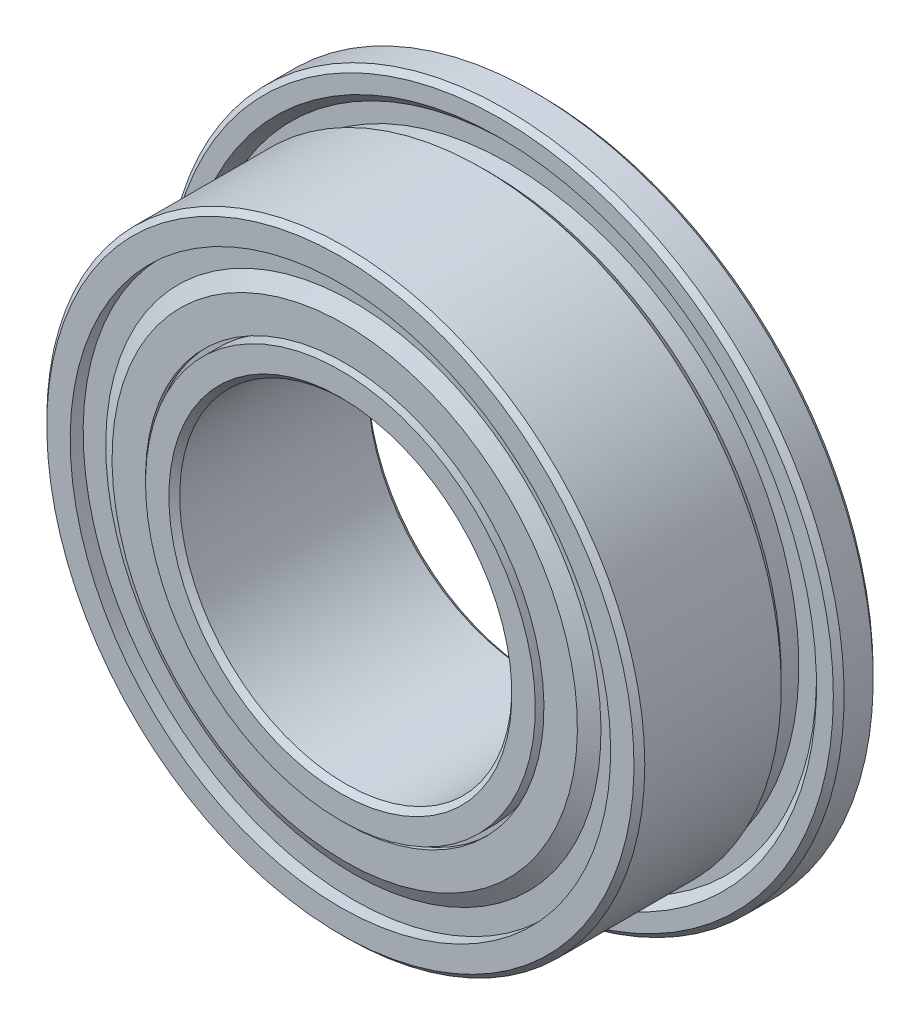
SolidWorks part; units mm, degrees
ref_plane "Front Plane" through (0, 0, 0) normal (0, 0, 1) x (1, 0, 0)
ref_plane "Top Plane" through (0, 0, 0) normal (0, 1, 0) x (1, 0, 0)
ref_plane "Right Plane" through (0, 0, 0) normal (1, 0, 0) x (0, 0, -1)
sketch "Sketch1" plane through (0, 0, 0) normal (1, 0, 0) x (0, 0, -1)
  line L0 (0, 4.5) -> (0, -4.5) construction
  line L1 (-1.5, 4.5) -> (1.5, 4.5) construction
  line L2 (0, 0) -> (1.5, 0) construction
  line L3 (1.5, 5.1) -> (1.5, -5.1) construction
  line L4 (1.5, -5.1) -> (0.9, -5.1) construction
  line L5 (1.5, 2.5) -> (0, 2.5) construction
  line L6 (1.5, 2.5) -> (1.5, -2.5) construction
  dimension "OD" = 9
  dimension "Width" = 3
  dimension "Flange Thickness" = 0.6
  dimension "ID" = 5
  dimension "Flange OD" = 10.2
sketch "Sketch2" plane through (0, 0, 0) normal (1, 0, 0) x (0, 0, -1)
  line L0 (1.5, 5.1) -> (0.9, 5.1)
  line L1 (0.9, 5.1) -> (0.9, 4.7652)
  line L2 (0.6348, 4.5) -> (-1.5, 4.5)
  line L3 (-1.5, 4.5) -> (-1.5, 3.85)
  line L4 (-1.5, 3.85) -> (-0.4873, 3.85)
  line L5 (1.5, 5.1) -> (1.5, -5.1) construction
  line L6 (1.5, 3.85) -> (1.5, 5.1)
  line L7 (1.5, 2.5) -> (-1.5, 2.5)
  line L8 (-1.5, 2.5) -> (-1.5, 3.15)
  line L9 (-1.5, 3.15) -> (-0.4873, 3.15)
  line L10 (1.5, 3.15) -> (1.5, 2.5)
  line L11 (0, 4.5) -> (0, 2.5) construction
  line L12 (-0.6, 3.5) -> (0.6, 3.5) construction
  line L13 (0.4873, 3.85) -> (1.5, 3.85)
  line L14 (0.4873, 3.15) -> (1.5, 3.15)
  line L15 (0.9, 4.7652) -> (1.0326, 4.6326)
  line L16 (1.0326, 4.6326) -> (1.0326, 4.3674)
  line L17 (1.0326, 4.3674) -> (0.7674, 4.3674)
  line L18 (0.7674, 4.3674) -> (0.6348, 4.5)
  line L19 (0.9, 4.5) -> (1.0326, 4.3674) construction
  line L20 (1.0326, 4.6326) -> (0.7674, 4.3674) construction
  line L21 (0.6348, 4.5) -> (0.9, 4.5) construction
  line L22 (0.9, 4.5) -> (0.9, 4.7652) construction
  line L23 (-1.5, 0) -> (1.5, 0) construction
  circle A0 centre (0, 3.5) radius 0.6 construction
  arc A1 (-0.4873, 3.85) -> (0.4873, 3.85) centre (0, 3.5) cw
  arc A2 (-0.4873, 3.15) -> (0.4873, 3.15) centre (0, 3.5) ccw
  dimension "Ball Dia." = 1.2
  dimension "D2" = 135
  dimension "D3" = 0.375
  dimension "Race Thikness" = 0.65
  dimension "D4" = 0.7
revolve "Revolve1" add sketch "Sketch2" angle 360 about L2
fillet "Fillet1" radius 0.0813 3 edges at (0, -5.1, -1.5) (0, -5.1, -0.9) (0, -4.5, 1.5) profile chamfer
sketch "Sketch3" plane through (0, 0, 0) normal (0, 0, 1) x (1, 0, 0)
  line L0 (-2.5, 0) -> (2.5, 0) construction
  line L1 (-4.5, 0) -> (4.5, 0) construction
  point P5 (0, 0)
  dimension "ID2" = 5
  dimension "OD2" = 9
fillet "Fillet2" radius 0.0813 2 edges at (0, -2.5, -1.5) (0, -2.5, 1.5) profile chamfer
sketch "Sketch7" plane through (0, 0, 0) normal (0, 0, 1) x (1, 0, 0)
  line L0 (0, 4.1) -> (0, 2.9)
  line L1 (0, 5.1) -> (0, -5.1) construction
  line L2 (-0.7134, 4.1) -> (0, 0) construction
  line L3 (0, 0) -> (0.7134, 4.1) construction
  line L4 (0.7134, 4.1) -> (-0.7134, 4.1) construction
  circle A0 centre (0, 3.5) radius 0.6 construction
  circle A1 centre (0, 0) radius 4.1 construction
  circle A2 centre (0, 0) radius 2.9 construction
  arc A4 (0, 4.1) -> (0, 2.9) centre (0, 3.5) ccw
  dimension "D1" = 19.742
revolve "Revolve3" add sketch "Sketch7" angle 360 about L0
pattern_circular "CirPattern3" count 14 over 360 about axis through (0, 0, 0) along (0, 0, 1) of bodies 107
sketch "Sketch8" plane through (0, 0, 0) normal (1, 0, 0) x (0, 0, -1)
  line L1 (-1.5, 3.85) -> (-1.24, 3.85)
  line L2 (-1.5, 3.85) -> (-1.5, 4.0667)
  line L3 (-1.5, 4.0667) -> (-1.24, 4.0667)
  line L4 (-1.24, 3.85) -> (-1.24, 4.0667)
  line L5 (1.5, 3.85) -> (1.24, 3.85)
  line L6 (1.5, 3.85) -> (1.5, 4.0667)
  line L7 (1.5, 4.0667) -> (1.24, 4.0667)
  line L8 (1.24, 3.85) -> (1.24, 4.0667)
  line L9 (1.5, 3.15) -> (1.24, 3.15)
  line L10 (1.5, 3.15) -> (1.5, 2.9333)
  line L11 (1.5, 2.9333) -> (1.24, 2.9333)
  line L12 (1.24, 3.15) -> (1.24, 2.9333)
  line L13 (-1.5, 3.15) -> (-1.24, 3.15)
  line L14 (-1.5, 3.15) -> (-1.5, 2.9333)
  line L15 (-1.5, 2.9333) -> (-1.24, 2.9333)
  line L16 (-1.24, 3.15) -> (-1.24, 2.9333)
  dimension "D1" = 0.2167
  dimension "D2" = 0.26
revolve "Cut-Revolve1" cut sketch "Sketch8" angle 360 about L2
sketch "Sketch9" plane through (0, 0, 0) normal (1, 0, 0) x (0, 0, -1)
  line L0 (-1.24, 4.0667) -> (-1.24, 3.7095)
  line L1 (-1.24, 3.7095) -> (-1.37, 3.4844)
  line L2 (-1.37, 3.4844) -> (-1.37, 2.9983)
  line L3 (1.37, 2.9983) -> (1.37, 2.9333) construction
  line L4 (1.24, 4.0667) -> (1.24, 3.7095)
  line L5 (1.24, 3.7095) -> (1.37, 3.4844)
  line L6 (1.37, 3.4844) -> (1.37, 2.9983)
  line L7 (1.5, 2.9333) -> (1.24, 2.9333) construction
  line L8 (-1.305, 4.0667) -> (-1.305, 3.7269)
  line L9 (-1.305, 3.7269) -> (-1.435, 3.5018)
  line L10 (-1.435, 3.5018) -> (-1.435, 2.9983)
  line L11 (-1.24, 4.0667) -> (-1.305, 4.0667)
  line L12 (-1.37, 2.9983) -> (-1.435, 2.9983)
  line L13 (1.305, 4.0667) -> (1.305, 3.7269)
  line L14 (1.305, 3.7269) -> (1.435, 3.5018)
  line L15 (1.435, 3.5018) -> (1.435, 2.9983)
  line L16 (1.24, 4.0667) -> (1.305, 4.0667)
  line L17 (1.37, 2.9983) -> (1.435, 2.9983)
  line L18 (-1.24, 3.7095) -> (-1.24, 2.5308) construction
  line L19 (1.24, 3.7095) -> (1.24, 4.0667) construction
  line L20 (-1.24, 2.9333) -> (-1.5, 2.9333) construction
  line L22 (-1.37, 2.9983) -> (-1.37, 2.9333) construction
  dimension "D2" = 150
  dimension "D1" = 150
  dimension "D5" = 0.26
  dimension "D3" = 0.065
  dimension "D4" = 0.065
  dimension "D6" = 0.3571
revolve "Revolve4" add sketch "Sketch9" angle 360 about L2
equation "\"D1@Fillet1\"=\"Race Thikness@Sketch2\"/8"
equation "\"ID2@Sketch3\" = \"ID@Sketch1\""
equation "\"OD2@Sketch3\" = \"OD@Sketch1\""
equation "\"D1@Fillet2\"=\"Race Thikness@Sketch2\"/8"
equation "\"D1@CirPattern3\"=360/\"D1@Sketch7\"-4"
equation "\"D1@Sketch8\"=\"Race Thikness@Sketch2\"/3"
equation "\"D2@Sketch8\"=\"Race Thikness@Sketch2\"/2.5"
equation "\"D3@Sketch9\"=\"D5@Sketch9\"/4"
equation "\"D4@Sketch9\"=\"D5@Sketch9\"/4"
equation "\"D1@Sketch9\"=\"D2@Sketch9\""
equation "\"Ball Dia.@Sketch2\" = \"D1@Sketch2\"*.5"
equation "\"D4@Sketch2\"=((\"OD@Sketch1\"-\"ID@Sketch1\")/2)*.35"
